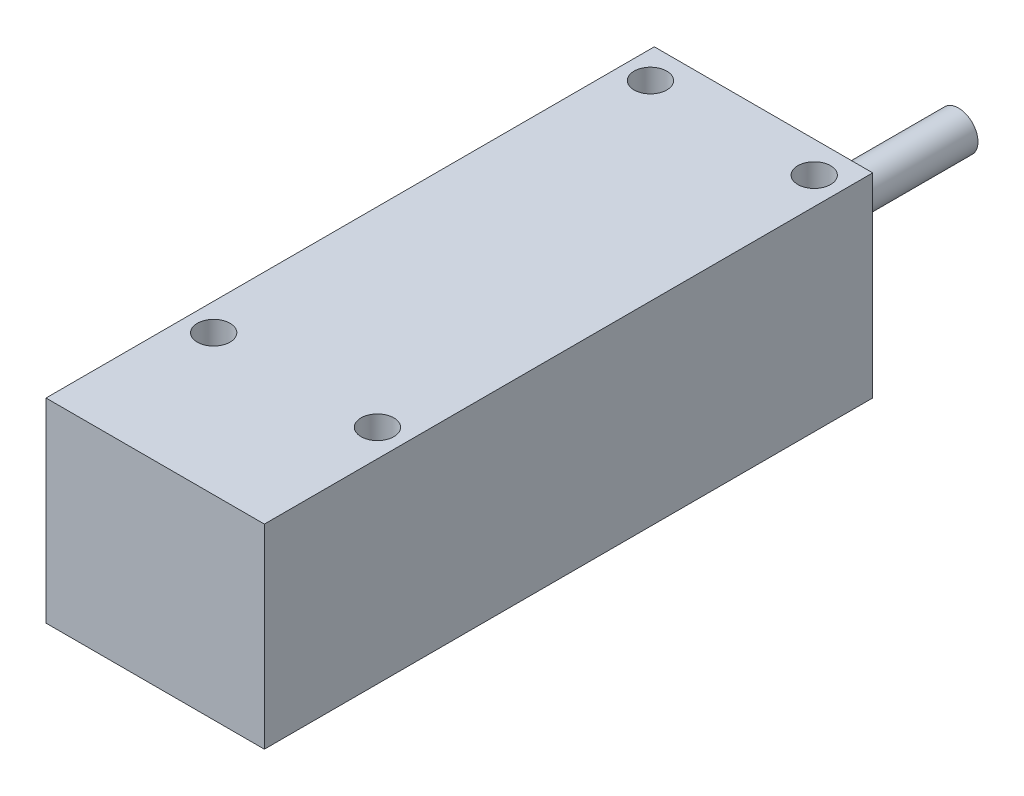
SolidWorks part; units mm, degrees
ref_plane "Front Plane" through (0, 0, 0) normal (0, 0, 1) x (1, 0, 0)
ref_plane "Top Plane" through (0, 0, 0) normal (0, 1, 0) x (1, 0, 0)
ref_plane "Right Plane" through (0, 0, 0) normal (1, 0, 0) x (0, 0, -1)
sketch "Sketch1" plane through (0, 0, 0) normal (0, 0, 1) x (1, 0, 0)
  line L1 (14, -12.5) -> (-14, -12.5)
  line L2 (14, -12.5) -> (14, 12.5)
  line L3 (14, 12.5) -> (-14, 12.5)
  line L4 (-14, -12.5) -> (-14, 12.5)
  line L5 (14, -12.5) -> (-14, 12.5) construction
  line L6 (14, 12.5) -> (-14, -12.5) construction
  point P0 (0, 0)
  dimension "D1" = 28
  dimension "D2" = 25
extrude "Boss-Extrude1" add sketch "Sketch1" along normal mid plane 78
sketch "Sketch2" plane through (0, 12.5, 0) normal (0, 1, 0) x (1, 0, 0)
  circle A0 centre (10.5, 35) radius 2.1
  circle A1 centre (10.5, -21) radius 2.1
  dimension "D1" = 4.2
  dimension "D3" = 10.5
  dimension "D4" = 35
  dimension "D2" = 56
extrude "Cut-Extrude1" cut sketch "Sketch2" against normal through all
mirror "Mirror1" about plane through (0, 0, 0) normal (1, 0, 0) of "Cut-Extrude1"
sketch "Sketch3" plane through (0, 0, -39) normal (0, 0, -1) x (-1, 0, 0)
  line L0 (14, -12.5) -> (-14, -12.5) construction
  circle A0 centre (0, -2.3) radius 2.5
  dimension "D1" = 5
  dimension "D2" = 10.2
extrude "Boss-Extrude2" add sketch "Sketch3" along normal blind 25
